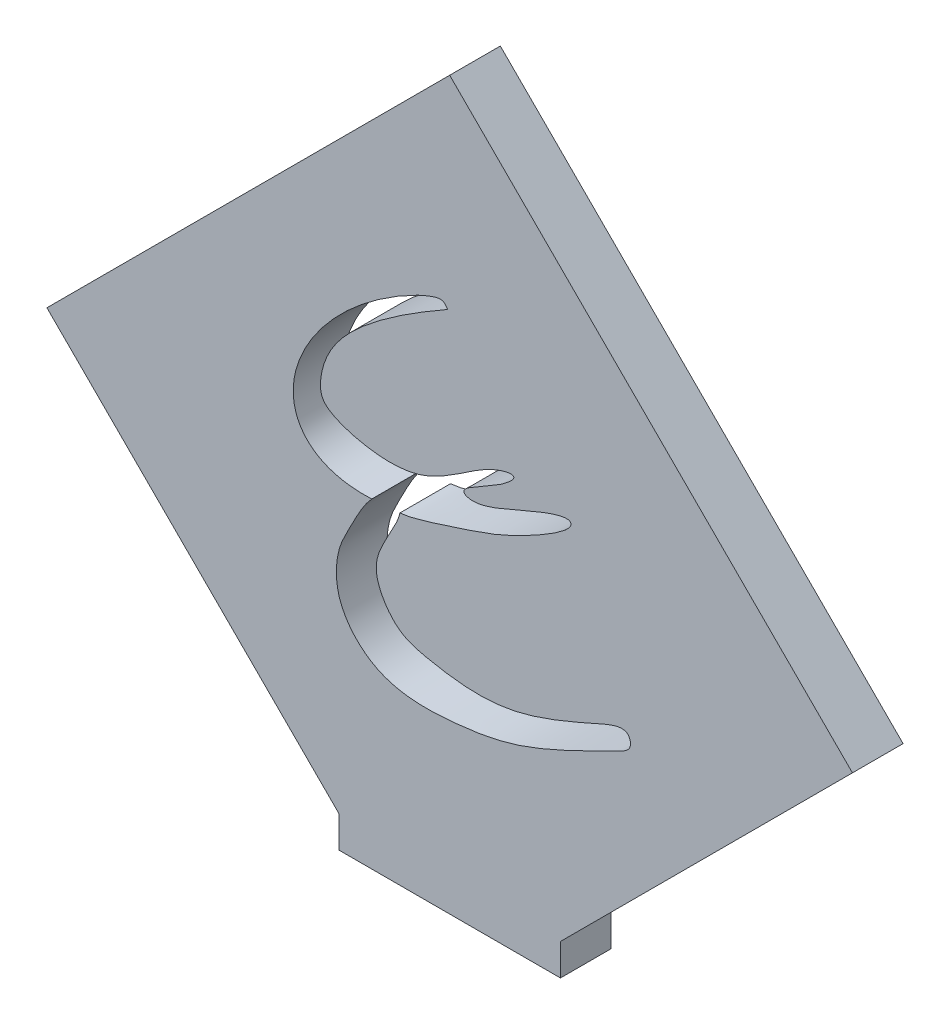
SolidWorks part; units mm, degrees
other "Marquage1"
sketch "Esquisse2" plane through (-63.6396, -63.6396, 0) normal (0, 0, 1) x (1, 0, 0)
ref_plane "Plan de face" through (0, 0, 0) normal (0, 0, 1) x (1, 0, 0)
ref_plane "Plan de dessus" through (0, 0, 0) normal (0, 1, 0) x (1, 0, 0)
ref_plane "Plan de droite" through (0, 0, 0) normal (1, 0, 0) x (0, 0, -1)
sketch "Esquisse1" plane through (0, 0, 0) normal (0, 0, 1) x (1, 0, 0)
  line L1 (-63.7089, 0.0693) -> (-0.0693, 63.7089)
  line L2 (-63.7089, 0.0693) -> (-17.5693, -46.0703)
  line L3 (17.4307, -46.0703) -> (63.5703, 0.0693)
  line L4 (-0.0693, 63.7089) -> (63.5703, 0.0693)
  line L5 (-45, 45) -> (45, -45) construction
  line L6 (-45, -45) -> (45, 45) construction
  line L9 (-17.5693, -46.0703) -> (-17.5693, -51.0703)
  line L10 (-17.5693, -51.0703) -> (17.4307, -51.0703)
  line L11 (17.4307, -46.0703) -> (17.4307, -51.0703)
  ellipse E0 centre (-1.5822, 17.3885) end of major axis (20.499, 30.8658) minor radius 13.7135 (-5.1155, 31.0925) -> (-12.3825, -0.4317) ccw
  spline S0 degree 3 poles (-5.1155, 31.0925) (-3.5885, 31.7841) (-1.2398, 32.8411) (-0.6189, 31.8484) (-0.3997, 31.4941) knots 0 0 0 0 0.64893 1 1 1 1
  spline S1 degree 3 poles (-7.9444, -0.124) (-7.3555, -0.0447) (-6.1593, 0.0036) (4.4332, 3.3711) (10.6507, 5.8096) (19.0657, 10.6778) (19.2405, 12.799) (13.1416, 10.9757) (4.6749, 6.5612) (0.7202, 8.0267) (7.3469, 10.9155) (11.5804, 14.6383) (4.7865, 13.0544) (-3.9741, 4.9104) (-15.5401, 6.4503) (-19.9411, 8.609) (-20.8039, 11.0689) (-19.1726, 19.2973) (-9.0536, 26.571) (-0.3997, 31.4941) knots 0 0 0 0 0.031256 0.106777 0.174945 0.245286 0.267298 0.321808 0.398015 0.429948 0.488178 0.533802 0.581225 0.664297 0.742642 0.792033 0.826166 0.887072 1 1 1 1
  spline S2 degree 3 poles (-12.3825, -0.4317) (-13.7986, -1.9706) (-15.7868, -6.0936) (-17.9406, -9.8731) (-18.3487, -16.8741) (-13.3508, -22.9959) (-6.5516, -25.0576) (1.881, -24.5459) (11.7791, -22.9525) (25.0049, -16.1856) (28.9395, -14.3898) (27.9933, -11.1564) (21.7572, -14.0903) (11.1301, -18.5906) (2.768, -18.9579) (-3.459, -17.9065) (-8.244, -16.7244) (-11.6011, -11.982) (-12.0818, -7.1933) (-8.193, -1.8116) (-7.9444, -0.124) knots 0 0 0 0 0.055003 0.100403 0.155064 0.213545 0.269817 0.331099 0.401224 0.484629 0.525513 0.554104 0.605282 0.680677 0.74304 0.79647 0.843344 0.892769 0.939895 1 1 1 1
  point P0 (0, 0)
  point P10 (-1.5128, 17.3191)
  point P11 (20.5683, 30.7964)
  point P12 (5.6316, 5.6137)
  point P13 (-5.0462, 31.0232)
  point P14 (-12.3825, -0.4317)
  point P15 (-24.4213, 10.4175)
  point P16 (21.3957, 24.2207)
  dimension "D1" = 90
  dimension "D2" = 90
  dimension "D3" = 5
  dimension "D5" = 35
  dimension "D6" = 63.6396
  dimension "D7" = 63.6396
  dimension "D10" = 32.2149
  dimension "D11" = 51.3264
extrude "Boss.-Extru.1" add sketch "Esquisse1" along normal blind 8
